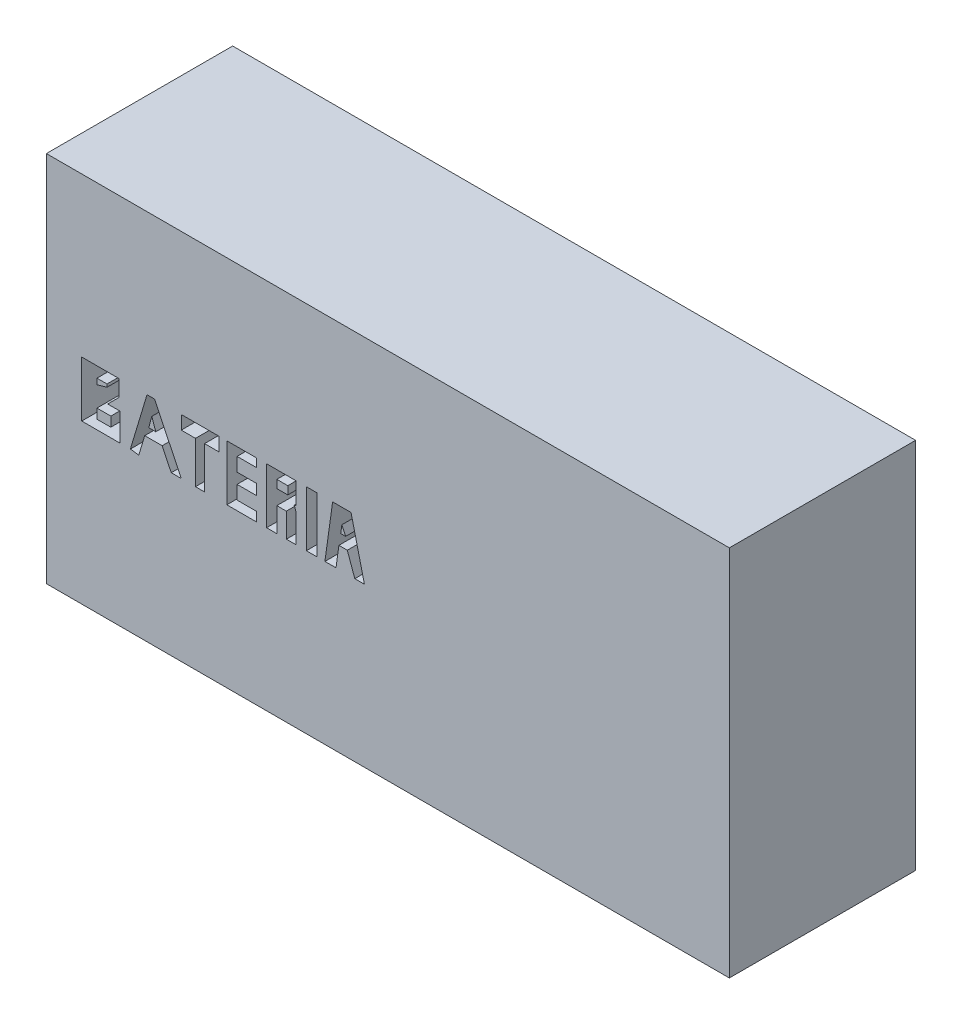
SolidWorks part; units mm, degrees
material "Liga de magnésio"
ref_plane "Plano frontal" through (0, 0, 0) normal (0, 0, 1) x (1, 0, 0)
ref_plane "Plano superior" through (0, 0, 0) normal (0, 1, 0) x (1, 0, 0)
ref_plane "Plano direito" through (0, 0, 0) normal (1, 0, 0) x (0, 0, -1)
sketch "Esboço1" plane through (0, 0, 0) normal (0, 0, 1) x (1, 0, 0)
  line L1 (0, 0) -> (55, 0)
  line L2 (0, 0) -> (0, 30)
  line L3 (0, 30) -> (55, 30)
  line L4 (55, 0) -> (55, 30)
  dimension "D1" = 55
  dimension "D2" = 30
extrude "Ressalto-extrusão1" add sketch "Esboço1" along normal blind 15
sketch "Esboço2" plane through (0, 0, 15) normal (0, 0, 1) x (1, 0, 0)
  line L0 (2.8468, 17.2328) -> (2.8468, 12.7672)
  line L1 (2.8468, 12.7672) -> (5.9454, 12.7672)
  line L2 (5.9454, 12.7672) -> (5.9454, 15)
  line L3 (5.9454, 15) -> (4.9354, 15)
  line L4 (4.9354, 15) -> (5.8468, 15.9113)
  line L5 (5.8468, 15.9113) -> (5.8468, 17.2328)
  line L6 (5.8468, 17.2328) -> (2.8468, 17.2328)
  line L7 (4.071, 16.3696) -> (4.071, 15.9113)
  line L8 (4.071, 16.3696) -> (4.88, 16.3696)
  line L9 (4.88, 16.3696) -> (4.88, 16.1405)
  line L10 (4.88, 16.1405) -> (4.071, 15.9113)
  line L11 (4.071, 14.2845) -> (4.071, 13.5068)
  line L12 (4.071, 13.5068) -> (5.189, 13.5068)
  line L13 (5.189, 13.5068) -> (5.189, 14.2845)
  line L14 (5.189, 14.2845) -> (4.071, 14.2845)
  line L15 (6.7607, 12.7672) -> (8.104, 17.2328)
  line L16 (8.104, 17.2328) -> (8.7121, 17.2328)
  line L17 (8.7121, 17.2328) -> (10.8614, 12.7672)
  line L18 (10.8614, 12.7672) -> (10.0554, 12.7672)
  line L19 (10.0554, 12.7672) -> (9.3251, 14.2845)
  line L20 (9.3251, 14.2845) -> (7.9202, 14.2845)
  line L21 (7.9202, 14.2845) -> (7.4323, 12.6628)
  line L22 (8.4858, 15.9113) -> (8.2454, 15)
  line L23 (8.2454, 15) -> (8.811, 15)
  line L24 (8.811, 15) -> (8.4858, 15.9113)
  line L25 (10.8614, 17.2328) -> (10.8614, 16.1405)
  line L26 (10.8614, 16.1405) -> (12.0068, 16.1405)
  line L27 (12.0068, 16.1405) -> (12.0068, 12.7672)
  line L28 (12.0068, 12.7672) -> (12.7406, 12.7672)
  line L29 (12.7406, 12.7672) -> (12.7406, 16.1405)
  line L30 (12.7406, 16.1405) -> (13.8874, 16.1405)
  line L31 (13.8874, 16.1405) -> (13.8874, 17.2328)
  line L32 (13.8874, 17.2328) -> (10.8614, 17.2328)
  line L33 (14.5312, 17.2328) -> (14.5312, 12.7672)
  line L34 (14.5312, 12.7672) -> (16.9052, 12.7672)
  line L35 (16.9052, 12.7672) -> (16.9052, 13.5068)
  line L36 (16.9052, 13.5068) -> (15.3561, 13.5068)
  line L37 (15.3561, 13.5068) -> (15.3561, 14.6049)
  line L38 (15.3561, 14.6049) -> (16.9052, 14.6049)
  line L39 (16.9052, 14.6049) -> (16.9052, 15.4557)
  line L40 (16.9052, 15.4557) -> (15.3561, 15.4557)
  line L41 (15.3561, 15.4557) -> (15.3561, 16.5565)
  line L42 (15.3561, 16.5565) -> (16.9052, 16.5565)
  line L43 (16.9052, 16.5565) -> (16.9052, 17.2328)
  line L44 (16.9052, 17.2328) -> (14.5312, 17.2328)
  line L45 (17.7329, 17.2328) -> (17.7329, 12.7672)
  line L46 (17.7329, 12.7672) -> (18.558, 12.7672)
  line L47 (18.558, 12.7672) -> (18.558, 14.7231)
  line L48 (18.558, 14.7231) -> (19.3242, 14.7231)
  line L49 (19.3242, 14.7231) -> (19.3242, 12.7672)
  line L50 (19.3242, 12.7672) -> (20.1199, 12.7672)
  line L51 (20.1199, 12.7672) -> (20.1199, 15)
  line L52 (20.1199, 15) -> (19.9573, 15.4557)
  line L53 (19.9573, 15.4557) -> (20.1199, 15.5137)
  line L54 (20.1199, 15.5137) -> (20.1199, 17.2328)
  line L55 (20.1199, 17.2328) -> (17.7329, 17.2328)
  line L56 (18.558, 16.5565) -> (18.558, 15.9113)
  line L57 (18.558, 15.9113) -> (19.4407, 15.9113)
  line L58 (19.4407, 15.9113) -> (19.4407, 16.5565)
  line L59 (19.4407, 16.5565) -> (18.558, 16.5565)
  line L60 (20.9349, 17.2328) -> (20.9349, 12.7672)
  line L61 (20.9349, 12.7672) -> (21.7888, 12.7672)
  line L62 (21.7888, 12.7672) -> (21.7888, 17.2328)
  line L63 (21.7888, 17.2328) -> (20.9349, 17.2328)
  line L64 (23.0502, 17.2328) -> (22.4292, 12.7672)
  line L65 (22.4292, 12.7672) -> (23.3219, 12.7672)
  line L66 (23.3219, 12.7672) -> (23.5564, 14.4538)
  line L67 (23.5564, 14.4538) -> (24.234, 14.4538)
  line L68 (24.234, 14.4538) -> (24.8359, 12.7672)
  line L69 (24.8359, 12.7672) -> (25.6118, 12.7672)
  line L70 (25.6118, 12.7672) -> (24.5349, 17.2328)
  line L71 (24.5349, 17.2328) -> (23.0502, 17.2328)
  line L72 (23.7926, 16.0061) -> (23.7011, 15.3485)
  line L73 (23.7011, 15.3485) -> (24.0981, 15.3485)
  line L74 (24.0981, 15.3485) -> (23.7926, 16.0061)
  line L75 (0, 30) -> (0, 0) construction
  line L76 (0, 0) -> (55, 0) construction
  line L77 (55, 30) -> (0, 30) construction
  arc A0 (7.4323, 12.6628) -> (6.7607, 12.7672) centre (6.7207, 10.297) ccw
  dimension "D27" = 2.4705
  dimension "D1" = 3
  dimension "D2" = 4.4656
  dimension "D3" = 3.0986
  dimension "D4" = 2.2328
  dimension "D5" = 1.0099
  dimension "D6" = 1.3215
  dimension "D7" = 0.9113
  dimension "D8" = 0.809
  dimension "D9" = 0.2291
  dimension "D10" = 0.809
  dimension "D11" = 0.4583
  dimension "D12" = 0.8632
  dimension "D13" = 1.2242
  dimension "D14" = 1.118
  dimension "D15" = 0.7777
  dimension "D16" = 0.7777
  dimension "D17" = 0.7564
  dimension "D18" = 0.7396
  dimension "D19" = 2.8468
  dimension "D20" = 12.7672
  dimension "D21" = 0.608
  dimension "D22" = 4.9559
  dimension "D23" = 1.4049
  dimension "D24" = 1.6839
  dimension "D25" = 0.806
  dimension "D26" = 1.6217
  dimension "D28" = 4.4656
  dimension "D29" = 0.5656
  dimension "D30" = 0.9113
  dimension "D31" = 0.5656
  dimension "D32" = 0.7155
  dimension "D33" = 1.966
  dimension "D34" = 0.6733
  dimension "D35" = 0.7263
  dimension "D36" = 12.7672
  dimension "D37" = 16.742
  dimension "D38" = 16.742
  dimension "D39" = 7.9202
  dimension "D40" = 8.2454
  dimension "D41" = 3.3733
  dimension "D42" = 1.1454
  dimension "D43" = 3.026
  dimension "D44" = 1.1468
  dimension "D45" = 0.7338
  dimension "D46" = 12.0068
  dimension "D47" = 12.7672
  dimension "D48" = 1.0923
  dimension "D49" = 1.0923
  dimension "D50" = 2.374
  dimension "D51" = 0.6764
  dimension "D52" = 1.5492
  dimension "D53" = 1.1008
  dimension "D54" = 1.5492
  dimension "D55" = 0.8508
  dimension "D56" = 1.5492
  dimension "D57" = 1.5492
  dimension "D58" = 1.0981
  dimension "D59" = 0.7396
  dimension "D60" = 2.374
  dimension "D61" = 4.4656
  dimension "D62" = 0.8508
  dimension "D63" = 0.6764
  dimension "D64" = 0.8249
  dimension "D65" = 12.7672
  dimension "D66" = 14.5312
  dimension "D67" = 2.387
  dimension "D68" = 1.7191
  dimension "D69" = 0.1727
  dimension "D70" = 0.4557
  dimension "D71" = 2.2328
  dimension "D72" = 0.7662
  dimension "D73" = 1.9559
  dimension "D74" = 1.9559
  dimension "D75" = 0.7957
  dimension "D76" = 0.8251
  dimension "D77" = 4.4656
  dimension "D78" = 0.8826
  dimension "D79" = 0.6451
  dimension "D80" = 0.6764
  dimension "D81" = 0.6792
  dimension "D82" = 0.7957
  dimension "D83" = 0.8277
  dimension "D84" = 12.7672
  dimension "D85" = 0.8539
  dimension "D86" = 4.4656
  dimension "D87" = 0.8539
  dimension "D88" = 0.8151
  dimension "D89" = 7.917
  dimension "D90" = 0.6576
  dimension "D91" = 0.9043
  dimension "D92" = 0.397
  dimension "D93" = 1.4847
  dimension "D94" = 4.5936
  dimension "D95" = 0.7759
  dimension "D96" = 0.6775
  dimension "D97" = 1.6866
  dimension "D98" = 1.6866
  dimension "D99" = 0.8927
  dimension "D100" = 4.4656
  dimension "D101" = 12.7672
  dimension "D102" = 12.7672
  dimension "D103" = 0.6404
  dimension "D104" = 1.9123
extrude "Corte-extrusão1" cut sketch "Esboço2" against normal blind 17
